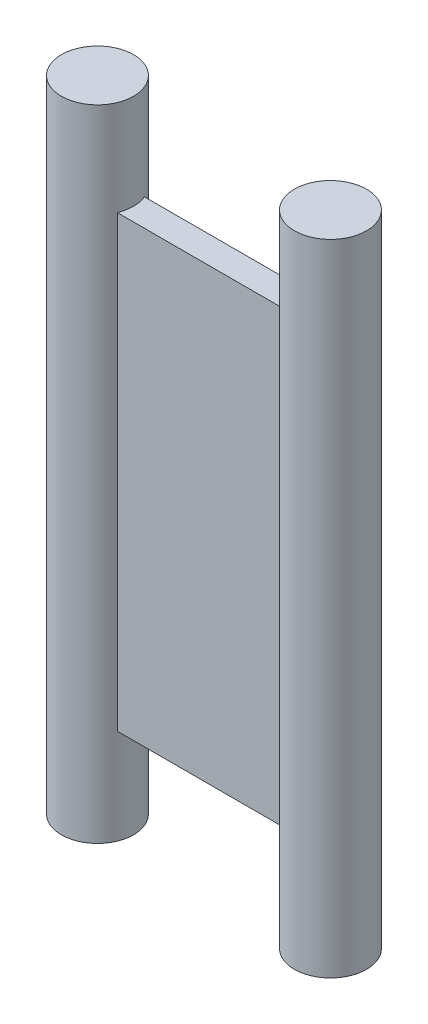
SolidWorks part; units mm, degrees
ref_plane "Front Plane" through (0, 0, 0) normal (0, 0, 1) x (1, 0, 0)
ref_plane "Top Plane" through (0, 0, 0) normal (0, 1, 0) x (1, 0, 0)
ref_plane "Right Plane" through (0, 0, 0) normal (1, 0, 0) x (0, 0, -1)
sketch "Sketch1" plane through (0, 0, 0) normal (0, 1, 0) x (1, 0, 0)
  line L1 (4.28, 0.5) -> (-4.28, 0.5)
  line L2 (4.28, 0.5) -> (4.28, -0.5)
  line L3 (4.28, -0.5) -> (-4.28, -0.5)
  line L4 (-4.28, 0.5) -> (-4.28, -0.5)
  line L5 (4.28, 0.5) -> (-4.28, -0.5) construction
  line L6 (4.28, -0.5) -> (-4.28, 0.5) construction
  point P0 (0, 0)
  dimension "D1" = 8.56
  dimension "D3" = 1
extrude "Boss-Extrude1" add sketch "Sketch1" along normal blind 16.5
ref_plane "Plane1" through (0, 8.25, 0) normal (0, 1, 0) x (1, 0, 0)
sketch "Sketch2" plane through (0, 8.25, 0) normal (0, 1, 0) x (1, 0, 0)
  line L0 (4.28, -0.5) -> (4.28, 0.5) construction
  line L1 (-4.28, 0.5) -> (-4.28, -0.5) construction
  line L2 (4.28, -0.5) -> (4.28, 0.5) construction
  line L3 (-4.28, 0.5) -> (-4.28, -0.5) construction
  circle A0 centre (-4.28, 0) radius 1.325
  circle A1 centre (4.28, 0) radius 1.325
  dimension "D1" = 2.65
extrude "Boss-Extrude2" add sketch "Sketch2" along normal mid plane 23.5
